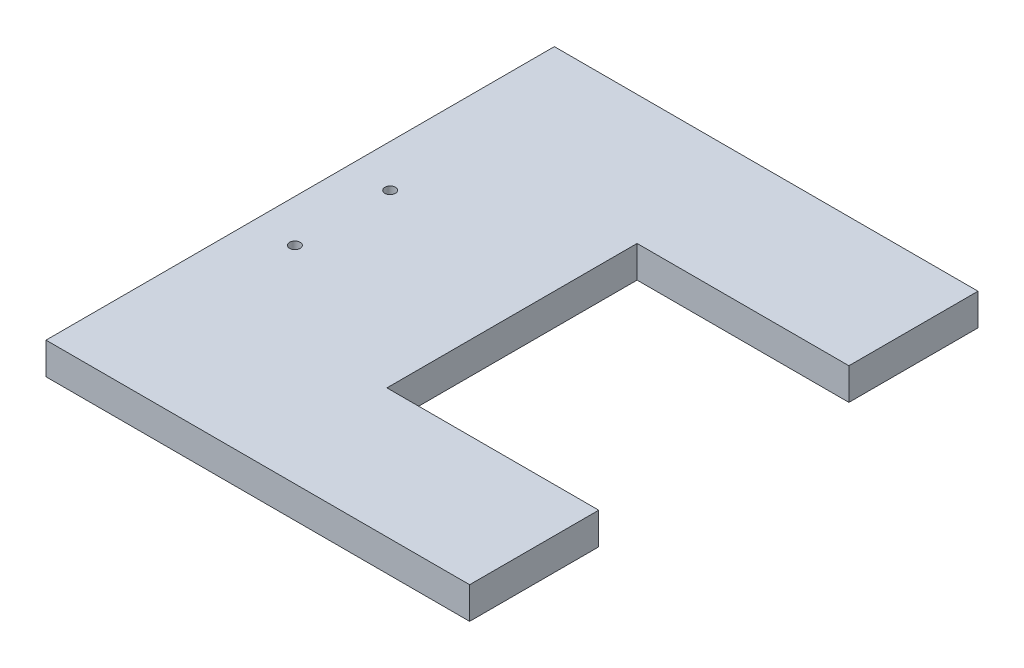
SolidWorks part; units mm, degrees
ref_plane "Front" through (0, 0, 0) normal (0, 0, 1) x (1, 0, 0)
ref_plane "Top" through (0, 0, 0) normal (0, 1, 0) x (1, 0, 0)
ref_plane "Right" through (0, 0, 0) normal (1, 0, 0) x (0, 0, -1)
sketch "Sketch1" plane through (0, 0, 0) normal (0, 1, 0) x (1, 0, 0)
  line L0 (-127, 0) -> (127, 0) construction
  line L1 (-127, 152.4) -> (127, 152.4)
  line L2 (-127, 152.4) -> (-127, -152.4)
  line L3 (-127, -152.4) -> (127, -152.4)
  line L4 (127, 152.4) -> (127, -152.4)
  line L5 (-127, 152.4) -> (127, -152.4) construction
  line L6 (-127, -152.4) -> (127, 152.4) construction
  line L12 (127, 75) -> (0, 75)
  line L13 (127, 75) -> (127, -75)
  line L14 (127, -75) -> (0, -75)
  line L15 (0, 75) -> (0, -75)
  point P0 (0, 0)
  point P13 (0, 0)
  dimension "D1" = 304.8
  dimension "D2" = 254
  dimension "D3" = 127
  dimension "D4" = 150
  dimension "D5" = 77.4
extrude "Boss-Extrude2" add sketch "Sketch1" along normal blind 19.05 contours L15 L12 L4 L1 L2 L3 L14
sketch "Sketch3" plane through (0, 19.05, 0) normal (0, 1, 0) x (1, 0, 0)
  line L0 (0, 0) -> (-127, 0)
  line L1 (0, 75) -> (0, -75) construction
  line L2 (-127, 152.4) -> (-127, -152.4) construction
  line L3 (-101.6, 28.575) -> (-101.6, -28.575) construction
  circle A0 centre (-101.6, 28.575) radius 3.175
  circle A1 centre (-101.6, -28.575) radius 3.175
  point P10 (-101.6, 0)
  point P11 (-239.995, -11.25)
  dimension "D1" = 57.15
  dimension "D2" = 6.35
  dimension "D3" = 25.4
extrude "Cut-Extrude1" cut sketch "Sketch3" against normal through all
